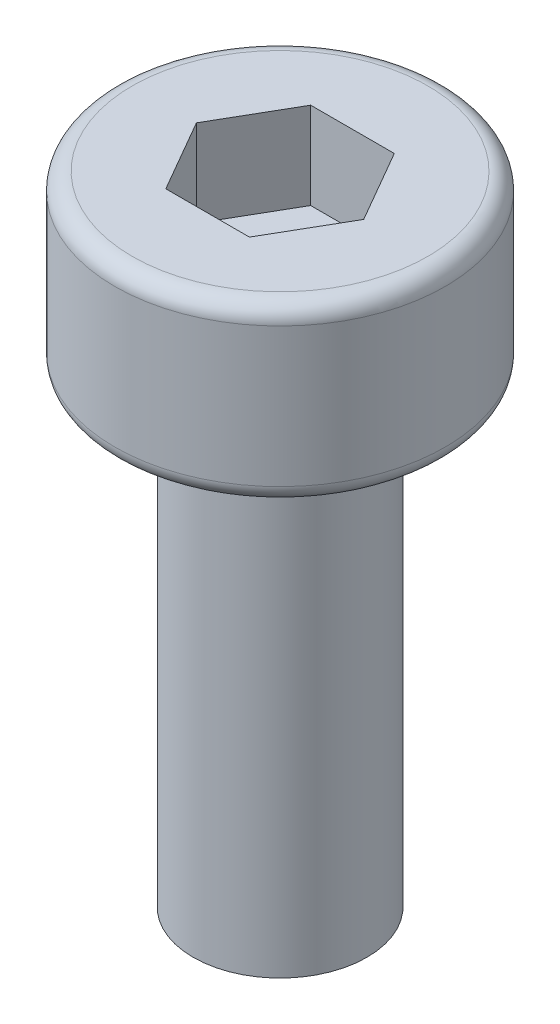
SolidWorks part; units mm, degrees
material "AISI 304"
ref_plane "前视基准面" through (0, 0, 0) normal (0, 0, 1) x (1, 0, 0)
ref_plane "上视基准面" through (0, 0, 0) normal (0, 1, 0) x (1, 0, 0)
ref_plane "右视基准面" through (0, 0, 0) normal (1, 0, 0) x (0, 0, -1)
sketch "草图1" plane through (0, 0, 0) normal (0, 1, 0) x (1, 0, 0)
  circle A0 centre (0, 0) radius 2.85
  dimension "D1" = 5.7
extrude "凸台-拉伸1" add sketch "草图1" along normal blind 3
sketch "草图2" plane through (0, 0, 0) normal (0, -1, 0) x (1, 0, 0)
  circle A0 centre (0, 0) radius 1.5
extrude "凸台-拉伸2" add sketch "草图2" along normal blind 8
fillet "圆角1" radius 0.3 2 edges at (0, 0, 2.85) (0, 3, 2.85)
sketch "草图3" plane through (0, 3, 0) normal (0, 1, 0) x (1, 0, 0)
  line L1 (-1.4434, 0) -> (-0.7217, -1.25)
  line L2 (-0.7217, -1.25) -> (0.7217, -1.25)
  line L3 (0.7217, -1.25) -> (1.4434, 0)
  line L4 (1.4434, 0) -> (0.7217, 1.25)
  line L5 (0.7217, 1.25) -> (-0.7217, 1.25)
  line L6 (-0.7217, 1.25) -> (-1.4434, 0)
  circle A0 centre (0, 0) radius 1.25 construction
  dimension "D1" = 2.5
extrude "切除-拉伸1" cut sketch "草图3" against normal blind 1.5
